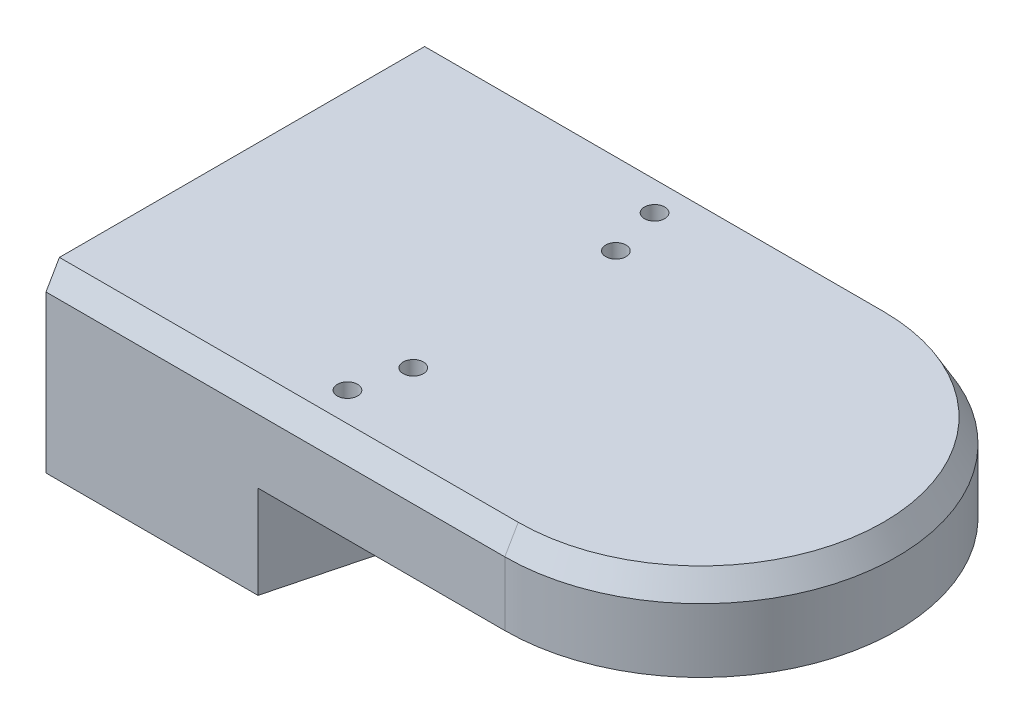
SolidWorks part; units mm, degrees
ref_plane "Alzado" through (0, 0, 0) normal (0, 0, 1) x (1, 0, 0)
ref_plane "Planta" through (0, 0, 0) normal (0, 1, 0) x (1, 0, 0)
ref_plane "Vista lateral" through (0, 0, 0) normal (1, 0, 0) x (0, 0, -1)
sketch "Croquis2" plane through (0, 0, 0) normal (0, 1, 0) x (1, 0, 0)
  line L0 (32.725, -35) -> (-35, -35) construction
  line L1 (52.1828, -19.7053) -> (38, 35) construction
  line L2 (-35, 35) -> (38, 35) construction
  line L3 (-35, -35) -> (-35, 35) construction
  line L4 (32.725, -35) -> (-35, -35)
  line L5 (52.1828, -19.7053) -> (38, 35)
  line L6 (-35, 35) -> (38, 35)
  line L7 (-35, -35) -> (-35, 35)
  arc A0 (32.5, -32.5) -> (54.1538, -20.7774) centre (46.5, -32.5) ccw construction
  arc A1 (52.1828, -19.7053) -> (32.5, -32.5) centre (46.5, -32.5) ccw construction
  arc A2 (32.5, -32.5) -> (32.725, -35) centre (46.5, -32.5) ccw
  arc A3 (52.1828, -19.7053) -> (32.5, -32.5) centre (46.5, -32.5) ccw
  circle A4 centre (1.5, -1.5) radius 24 construction
  circle A5 centre (1.5, -1.5) radius 24 construction
extrude "Saliente-Extruir2" add sketch "Croquis2" along normal blind 23
sketch "Croquis7" plane through (0, 23, 0) normal (0, 1, 0) x (1, 0, 0)
  circle A0 centre (1.5, -1.5) radius 24 construction
  circle A1 centre (1.5, -1.5) radius 24 construction
  circle A2 centre (1.5, -1.5) radius 20
  dimension "D1" = 40
extrude "Cortar-Extruir1" cut sketch "Croquis7" against normal blind 16 contours A2
sketch "Croquis8" plane through (0, 7, 0) normal (0, 1, 0) x (1, 0, 0)
  circle A0 centre (1.5, -1.5) radius 10.25
  circle A1 centre (1.5, -1.5) radius 20 construction
  dimension "D1" = 20.5
extrude "Cortar-Extruir2" cut sketch "Croquis8" against normal through all
sketch "Croquis9" plane through (0, 23, 0) normal (0, 1, 0) x (1, 0, 0)
  line L0 (-35, 35) -> (-35, -35) construction
  line L1 (38, 35) -> (-35, 35) construction
  line L2 (-35, 35) -> (-35, -100)
  line L4 (38, 35) -> (-35, 35)
  line L6 (46.5, -32.5) -> (-35, -32.5) construction
  line L7 (38, 35) -> (54.8494, -29.9904)
  line L9 (52.1828, -19.7053) -> (38, 35) construction
  line L10 (38, -100) -> (54.8494, -35.0096)
  line L11 (38, -100) -> (-35, -100)
  arc A0 (52.1828, -19.7053) -> (32.725, -35) centre (46.5, -32.5) ccw construction
  circle A2 centre (1.5, -1.5) radius 20 construction
  circle A3 centre (1.5, -1.5) radius 20
  arc A4 (52.1828, -19.7053) -> (32.725, -35) centre (46.5, -32.5) ccw construction
  circle A5 centre (46.5, -32.5) radius 3.075
  arc A6 (54.8494, -35.0096) -> (54.8494, -29.9904) centre (45.1694, -32.5) ccw
  circle A7 centre (1.5, -1.5) radius 10.25 construction
  circle A8 centre (1.5, -1.5) radius 10.25 construction
  circle A9 centre (1.5, -63.5) radius 10.25
  point P19 (55.5, -32.5)
  dimension "D1" = 10
  dimension "D2" = 6.15
extrude "Saliente-Extruir3" add sketch "Croquis9" along normal blind 32
sketch "Croquis10" plane through (0, 23, 0) normal (0, -1, 0) x (1, 0, 0)
  line L0 (46.5, 32.5) -> (-35, 32.5) construction
  line L1 (-35, -35) -> (-35, 35) construction
  circle A0 centre (1.5, 1.5) radius 20 construction
  circle A1 centre (1.5, 1.5) radius 20 construction
  circle A2 centre (1.5, 63.5) radius 20
extrude "Cortar-Extruir3" cut sketch "Croquis10" against normal through all from offset 7 offset against normal yes
sketch "Croquis11" plane through (0, 55, 0) normal (0, 1, 0) x (1, 0, 0)
  line L0 (46.5, -32.5) -> (123, -32.5) construction
  line L1 (38, 35) -> (-35, 35) construction
  line L2 (123, 35) -> (-35, 35)
  line L3 (-35, 35) -> (-35, -100)
  line L4 (-35, -100) -> (123, -100)
  arc A0 (123, -100) -> (123, 35) centre (123, -32.5) ccw
  circle A1 centre (46.5, -32.5) radius 3.075 construction
  circle A2 centre (1.5, -63.5) radius 20 construction
  circle A3 centre (1.5, -1.5) radius 20 construction
  circle A4 centre (46.5, -32.5) radius 3.075
  circle A5 centre (1.5, -63.5) radius 20
  circle A6 centre (1.5, -1.5) radius 20
  dimension "D1" = 76.5
extrude "Saliente-Extruir4" add sketch "Croquis11" along normal blind 20
sketch "Croquis12" plane through (0, 55, 0) normal (0, -1, 0) x (1, 0, 0)
  circle A0 centre (123, 32.5) radius 63
  dimension "D1" = 126
extrude "Cortar-Extruir4" cut sketch "Croquis12" against normal blind 3
sketch "Croquis13" plane through (0, 58, 0) normal (0, -1, 0) x (1, 0, 0)
  circle A0 centre (123, 32.5) radius 55
  circle A1 centre (123, 32.5) radius 63 construction
  dimension "D1" = 110
extrude "Cortar-Extruir5" cut sketch "Croquis13" against normal blind 10
sketch "Croquis14" plane through (0, 75, 0) normal (0, 1, 0) x (1, 0, 0)
  line L0 (-35, -100) -> (123, -100) construction
  line L1 (123, 35) -> (-35, 35) construction
  line L2 (-35, 35) -> (-35, -100) construction
  line L3 (-35, -100) -> (123, -100)
  line L4 (123, 35) -> (-35, 35)
  line L5 (-35, 35) -> (-35, -100)
  arc A0 (123, -100) -> (123, 35) centre (123, -32.5) ccw construction
  arc A1 (123, -100) -> (123, 35) centre (123, -32.5) ccw
extrude "Saliente-Extruir5" add sketch "Croquis14" along normal blind 10
chamfer "Chaflán1" distance 8 angle 30 3 edges at (44, 85, -35) (190.5, 85, 32.5) (44, 85, 100)
sketch "Croquis15" plane through (0, 68, 0) normal (0, -1, 0) x (1, 0, 0)
  circle A0 centre (123, 32.5) radius 6
  dimension "D1" = 12
extrude "Cortar-Extruir6" cut sketch "Croquis15" against normal blind 14.8
sketch "Croquis17" plane through (0, 0, 0) normal (0, -1, 0) x (1, 0, 0)
  line L0 (1.5, 1.5) -> (16.5, 1.5) construction
  line L1 (1.5, 1.5) -> (13.6244, 8.5) construction
  circle A0 centre (1.5, 1.5) radius 15 construction
  circle A1 centre (1.5, 1.5) radius 14 construction
  circle A2 centre (16.5, 1.5) radius 1.5
  circle A3 centre (-6, -11.4904) radius 1.5
  circle A4 centre (-6, 14.4904) radius 1.5
  circle A6 centre (13.6244, 8.5) radius 1.5
  circle A7 centre (1.5, -12.5) radius 1.5
  circle A8 centre (1.5, 1.5) radius 14 construction
  circle A9 centre (-10.6244, 8.5) radius 1.5
  circle A10 centre (1.5, 1.5) radius 14 construction
  point P13 (1.5, 1.5)
  point P22 (1.5, 1.5)
  dimension "D1" = 30
  dimension "D2" = 28
  dimension "D3" = 3
  dimension "D5" = 30
  dimension "D4" = 3
  dimension "D6" = 3
extrude "Cortar-Extruir7" cut sketch "Croquis17" against normal up to next
sketch "Croquis19" plane through (0, 23, 0) normal (0, -1, 0) x (1, 0, 0)
  line L0 (1.5, 63.5) -> (16.5, 63.5) construction
  line L1 (1.5, 63.5) -> (13.6244, 70.5) construction
  circle A0 centre (1.5, 63.5) radius 15 construction
  circle A1 centre (1.5, 63.5) radius 14 construction
  circle A2 centre (16.5, 63.5) radius 1.5
  circle A3 centre (-6, 50.5096) radius 1.5
  circle A4 centre (-6, 76.4904) radius 1.5
  circle A6 centre (13.6244, 70.5) radius 1.5
  circle A7 centre (1.5, 49.5) radius 1.5
  circle A8 centre (-10.6244, 70.5) radius 1.5
  point P13 (1.5, 63.5)
  point P20 (1.5, 63.5)
  dimension "D1" = 30
  dimension "D2" = 28
  dimension "D3" = 3
  dimension "D6" = 30
  dimension "D4" = 3
  dimension "D5" = 3
extrude "Cortar-Extruir9" cut sketch "Croquis19" against normal up to next
sketch "Croquis20" plane through (0, 0, 0) normal (0, -1, 0) x (1, 0, 0)
  line L1 (16.5, 1.5) -> (41.2646, 1.5) construction
  line L2 (46.3749, 21.211) -> (32.192, -33.4942)
  line L3 (42.3657, 5.7471) -> (39.7731, -4.2529)
  line L4 (39.4617, 9.5) -> (19.8303, 9.5)
  line L5 (36.8691, -6.5) -> (19.8303, -6.5)
  circle A0 centre (1.5, 1.5) radius 20 construction
  arc A1 (19.8303, -6.5) -> (19.8303, 9.5) centre (1.5, 1.5) ccw
  arc A2 (39.7731, -4.2529) -> (36.8691, -6.5) centre (36.8691, -3.5) cw
  arc A3 (42.3657, 5.7471) -> (39.4617, 9.5) centre (39.4617, 6.5) ccw
  dimension "D3" = 3
  dimension "D2" = 16
  dimension "D1" = 6
extrude "Cortar-Extruir10" cut sketch "Croquis20" against normal blind 50
sketch "Croquis21" plane through (0, 23, 0) normal (0, -1, 0) x (1, 0, 0)
  line L0 (19.8303, -6.5) -> (36.8691, -6.5) construction
  line L1 (39.7731, -4.2529) -> (42.3657, 5.7471) construction
  line L2 (39.4617, 9.5) -> (19.8303, 9.5) construction
  line L3 (19.8303, -6.5) -> (36.8691, -6.5) construction
  line L4 (39.7731, -4.2529) -> (42.3657, 5.7471) construction
  line L5 (39.4617, 9.5) -> (19.8303, 9.5) construction
  line L6 (46.5, 32.5) -> (-35, 32.5) construction
  line L7 (-35, -35) -> (-35, 35) construction
  line L8 (39.4617, 55.5) -> (19.8303, 55.5)
  line L9 (39.7731, 69.2529) -> (42.3657, 59.2529)
  line L10 (19.8303, 71.5) -> (36.8691, 71.5)
  arc A0 (36.8691, -6.5) -> (39.7731, -4.2529) centre (36.8691, -3.5) ccw construction
  arc A1 (42.3657, 5.7471) -> (39.4617, 9.5) centre (39.4617, 6.5) ccw construction
  arc A2 (19.8303, -6.5) -> (19.8303, 9.5) centre (1.5, 1.5) ccw construction
  arc A3 (36.8691, -6.5) -> (39.7731, -4.2529) centre (36.8691, -3.5) ccw construction
  arc A4 (42.3657, 5.7471) -> (39.4617, 9.5) centre (39.4617, 6.5) ccw construction
  arc A5 (19.8303, -6.5) -> (19.8303, 9.5) centre (1.5, 1.5) ccw construction
  arc A6 (19.8303, 71.5) -> (19.8303, 55.5) centre (1.5, 63.5) cw
  arc A7 (42.3657, 59.2529) -> (39.4617, 55.5) centre (39.4617, 58.5) cw
  arc A8 (36.8691, 71.5) -> (39.7731, 69.2529) centre (36.8691, 68.5) cw
extrude "Cortar-Extruir11" cut sketch "Croquis21" against normal blind 50
sketch "Croquis22" plane through (0, 0, 0) normal (0, -1, 0) x (1, 0, 0)
  circle A0 centre (-6, 14.4904) radius 3
  circle A1 centre (-10.6244, 8.5) radius 3
  circle A2 centre (-6, -11.4904) radius 3
  circle A3 centre (1.5, -12.5) radius 3
  circle A4 centre (16.5, 1.5) radius 3
  circle A5 centre (13.6244, 8.5) radius 3
  dimension "D1" = 6
extrude "Cortar-Extruir12" cut sketch "Croquis22" against normal blind 3
sketch "Croquis23" plane through (0, 23, 0) normal (0, -1, 0) x (1, 0, 0)
  circle A0 centre (-6, 76.4904) radius 3
  circle A1 centre (-10.6244, 70.5) radius 3
  circle A2 centre (-6, 50.5096) radius 3
  circle A3 centre (1.5, 49.5) radius 3
  circle A4 centre (16.5, 63.5) radius 3
  circle A5 centre (13.6244, 70.5) radius 3
  dimension "D1" = 6
extrude "Cortar-Extruir13" cut sketch "Croquis23" against normal blind 3
sketch "Croquis25" plane through (0, 23, 0) normal (0, -1, 0) x (1, 0, 0)
  line L0 (1.5, 63.5) -> (-35, 63.5) construction
  line L1 (-35, 35) -> (-35, 100) construction
  line L2 (-35, 35) -> (32.725, 35) construction
  circle A0 centre (-28.75, 63.5) radius 2.5
  circle A1 centre (29, 47) radius 2.5
  dimension "D1" = 5
  dimension "D2" = 6.25
  dimension "D3" = 64
  dimension "D4" = 12
extrude "Cortar-Extruir15" cut sketch "Croquis25" against normal blind 30
sketch "Croquis24" plane through (0, 0, 0) normal (0, -1, 0) x (1, 0, 0)
  line L0 (1.5, 1.5) -> (-35, 1.5) construction
  line L1 (-35, -35) -> (-35, 35) construction
  line L4 (-22, -22) -> (25, -22) construction
  line L5 (-22, -22) -> (-22, 25) construction
  line L6 (-22, 25) -> (25, 25) construction
  line L7 (25, -22) -> (25, 25) construction
  line L8 (-22, -22) -> (25, 25) construction
  line L9 (-22, 25) -> (25, -22) construction
  circle A0 centre (-28.75, 1.5) radius 2.5
  circle A1 centre (25, 25) radius 2.5
  dimension "D1" = 5
  dimension "D2" = 6.25
  dimension "D3" = 47
extrude "Cortar-Extruir14" cut sketch "Croquis24" against normal blind 30
sketch "Croquis26" plane through (0, 55, 0) normal (0, -1, 0) x (1, 0, 0)
  line L2 (49.616, 103.0115) -> (66.4653, 38.0212)
  line L3 (49.616, 103.0115) -> (66.4653, 38.0212) construction
  line L4 (-35, 95.3812) -> (123, 95.3812) construction
  line L5 (46.5, 32.5) -> (123, 32.5) construction
  circle A0 centre (54.1868, 85.3812) radius 2
  circle A1 centre (58.8535, 67.3812) radius 2
  circle A2 centre (58.8535, -2.3812) radius 2
  circle A3 centre (54.1868, -20.3812) radius 2
  dimension "D2" = 10
  dimension "D3" = 18
  dimension "D4" = 4
  dimension "D1" = 12
extrude "Cortar-Extruir16" cut sketch "Croquis26" against normal through all
sketch "Croquis27" plane through (0, 85, 0) normal (0, 1, 0) x (1, 0, 0)
  circle A0 centre (54.1868, 20.3812) radius 3.5
  circle A1 centre (58.8535, 2.3812) radius 3.5
  circle A2 centre (58.8535, -67.3812) radius 3.5
  circle A3 centre (54.1868, -85.3812) radius 3.5
  dimension "D1" = 7
extrude "Cortar-Extruir17" cut sketch "Croquis27" against normal blind 5
sketch "Croquis28" plane through (0, 55, 0) normal (0, -1, 0) x (1, 0, 0)
  line L0 (38, 100) -> (54.8494, 35.0096) construction
  line L1 (55.2228, 81.3853) -> (58.1654, 84.2804)
  line L2 (58.1654, 84.2804) -> (57.1294, 88.2764)
  line L3 (57.1294, 88.2764) -> (53.1508, 89.3771)
  line L4 (53.1508, 89.3771) -> (50.2082, 86.482)
  line L5 (50.2082, 86.482) -> (51.2442, 82.486)
  line L6 (51.2442, 82.486) -> (55.2228, 81.3853)
  line L7 (59.8894, 63.3853) -> (62.832, 66.2804)
  line L8 (62.832, 66.2804) -> (61.7961, 70.2764)
  line L9 (61.7961, 70.2764) -> (57.8175, 71.3771)
  line L10 (57.8175, 71.3771) -> (54.8749, 68.482)
  line L11 (54.8749, 68.482) -> (55.9109, 64.486)
  line L12 (55.9109, 64.486) -> (59.8894, 63.3853)
  line L13 (59.8894, 1.6147) -> (55.9109, 0.514)
  line L14 (55.9109, 0.514) -> (54.8749, -3.482)
  line L15 (54.8749, -3.482) -> (57.8175, -6.3771)
  line L16 (57.8175, -6.3771) -> (61.7961, -5.2764)
  line L17 (61.7961, -5.2764) -> (62.832, -1.2804)
  line L18 (62.832, -1.2804) -> (59.8894, 1.6147)
  line L19 (55.2228, -16.3853) -> (51.2442, -17.486)
  line L20 (51.2442, -17.486) -> (50.2082, -21.482)
  line L21 (50.2082, -21.482) -> (53.1508, -24.3771)
  line L22 (53.1508, -24.3771) -> (57.1294, -23.2764)
  line L23 (57.1294, -23.2764) -> (58.1654, -19.2804)
  line L24 (58.1654, -19.2804) -> (55.2228, -16.3853)
  line L25 (52.1828, 19.7053) -> (38, -35) construction
  circle A0 centre (54.1868, 85.3812) radius 3.575 construction
  circle A1 centre (58.8535, 67.3812) radius 3.575 construction
  circle A2 centre (58.8535, -2.3812) radius 3.575 construction
  circle A3 centre (54.1868, -20.3812) radius 3.575 construction
  dimension "D1" = 7.15
extrude "Cortar-Extruir18" cut sketch "Croquis28" against normal blind 3.25
sketch "Croquis29" plane through (0, 68, 0) normal (0, -1, 0) x (1, 0, 0)
  circle A0 centre (123, 32.5) radius 37.5 construction
  circle A1 centre (160.5, 32.5) radius 1.5
  circle A2 centre (141.75, 0.024) radius 1.5
  circle A3 centre (104.25, 0.024) radius 1.5
  circle A4 centre (85.5, 32.5) radius 1.5
  circle A5 centre (104.25, 64.976) radius 1.5
  circle A6 centre (141.75, 64.976) radius 1.5
  point P18 (123, 32.5)
  dimension "D1" = 75
  dimension "D2" = 3
  dimension "D3" = 6
extrude "Cortar-Extruir19" cut sketch "Croquis29" against normal blind 10
